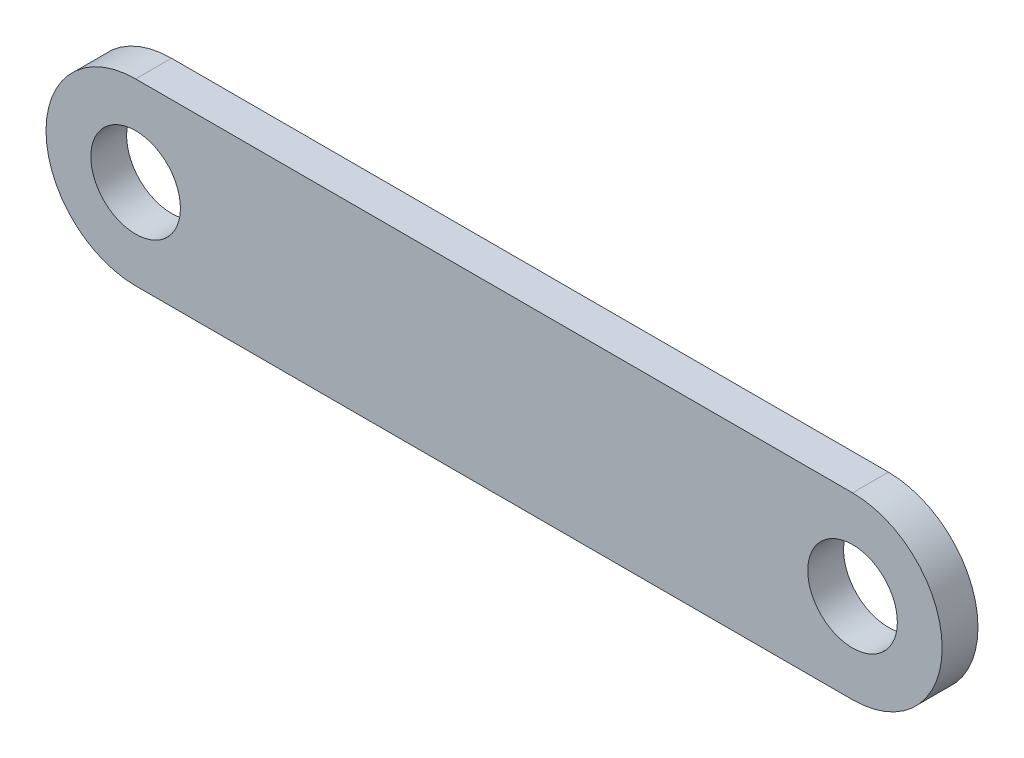
SolidWorks part; units mm, degrees
material "ABS"
ref_plane "正面" through (0, 0, 0) normal (0, 0, 1) x (1, 0, 0)
ref_plane "平面" through (0, 0, 0) normal (0, 1, 0) x (1, 0, 0)
ref_plane "右側面" through (0, 0, 0) normal (1, 0, 0) x (0, 0, -1)
sketch "ｽｹｯﾁ1" plane through (0, 0, 0) normal (0, 0, 1) x (1, 0, 0)
  line L0 (0, 0) -> (80, 0) construction
  line L1 (0, 10) -> (80, 10)
  line L2 (0, -10) -> (80, -10)
  arc A0 (0, 10) -> (0, -10) centre (0, 0) ccw
  arc A1 (80, -10) -> (80, 10) centre (80, 0) ccw
  circle A2 centre (0, 0) radius 5
  circle A3 centre (80, 0) radius 5
  point P3 (40, 0)
  dimension "D1" = 10
  dimension "D3" = 10
  dimension "D2" = 80
extrude "ﾎﾞｽ - 押し出し1" add sketch "ｽｹｯﾁ1" along normal blind 4
